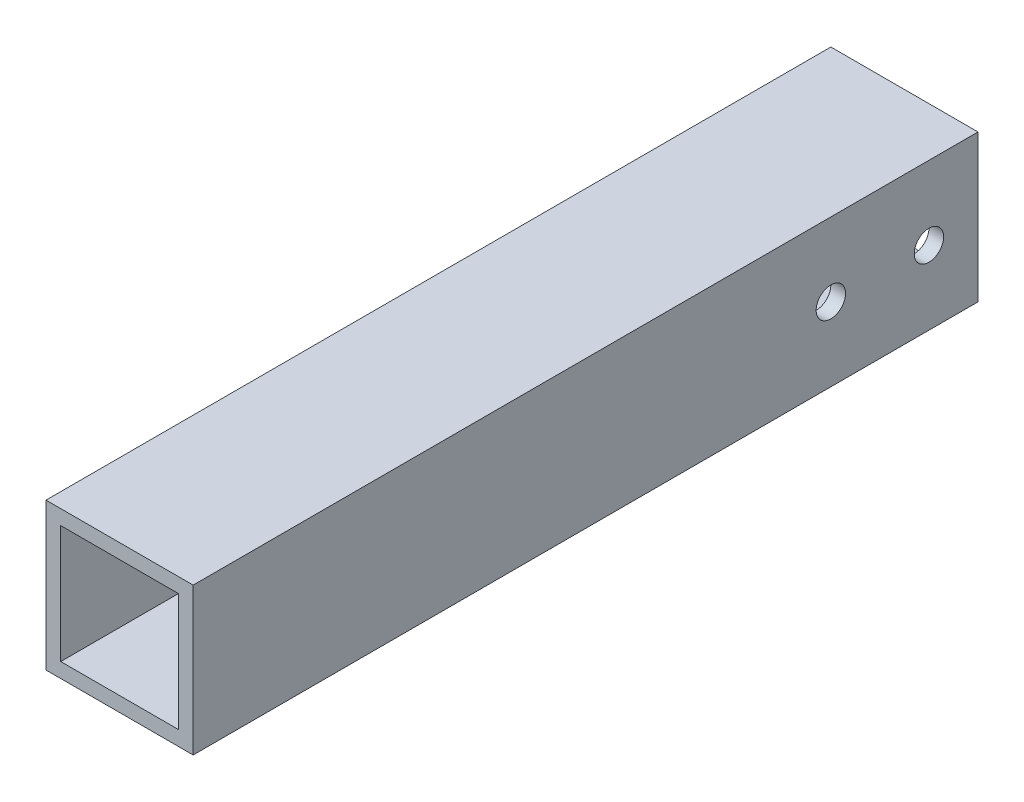
SolidWorks part; units mm, degrees
ref_plane "Plan de face" through (0, 0, 0) normal (0, 0, 1) x (1, 0, 0)
ref_plane "Plan de dessus" through (0, 0, 0) normal (0, 1, 0) x (1, 0, 0)
ref_plane "Plan de droite" through (0, 0, 0) normal (1, 0, 0) x (0, 0, -1)
sketch "Esquisse1" plane through (0, 0, 0) normal (0, 0, 1) x (1, 0, 0)
  line L1 (-7.5, -7.5) -> (7.5, -7.5)
  line L2 (-7.5, -7.5) -> (-7.5, 7.5)
  line L3 (-7.5, 7.5) -> (7.5, 7.5)
  line L4 (7.5, -7.5) -> (7.5, 7.5)
  line L5 (-7.5, -7.5) -> (7.5, 7.5) construction
  line L6 (-7.5, 7.5) -> (7.5, -7.5) construction
  point P0 (0, 0)
  dimension "D1" = 15
  dimension "D2" = 15
extrude "Extrusion1" add sketch "Esquisse1" along normal blind 80
sketch "Esquisse2" plane through (0, 0, 80) normal (0, 0, 1) x (1, 0, 0)
  line L0 (7.5, 7.5) -> (-7.5, 7.5) construction
  line L1 (-6, -6) -> (6, -6)
  line L2 (-6, -6) -> (-6, 6)
  line L3 (-6, 6) -> (6, 6)
  line L4 (6, -6) -> (6, 6)
  line L5 (-6, -6) -> (6, 6) construction
  line L6 (-6, 6) -> (6, -6) construction
  line L7 (7.5, -7.5) -> (7.5, 7.5) construction
  point P0 (0, 0)
  dimension "D1" = 1.5
  dimension "D2" = 1.5
extrude "Extrusion2" cut sketch "Esquisse2" against normal through all
sketch "Esquisse3" plane through (7.5, 0, 0) normal (1, 0, 0) x (0, 0, -1)
  circle A0 centre (-5, 0) radius 1.5
  circle A1 centre (-15, 0) radius 1.5
extrude "Enlèv. mat.-Extru.1" cut sketch "Esquisse3" against normal through all
